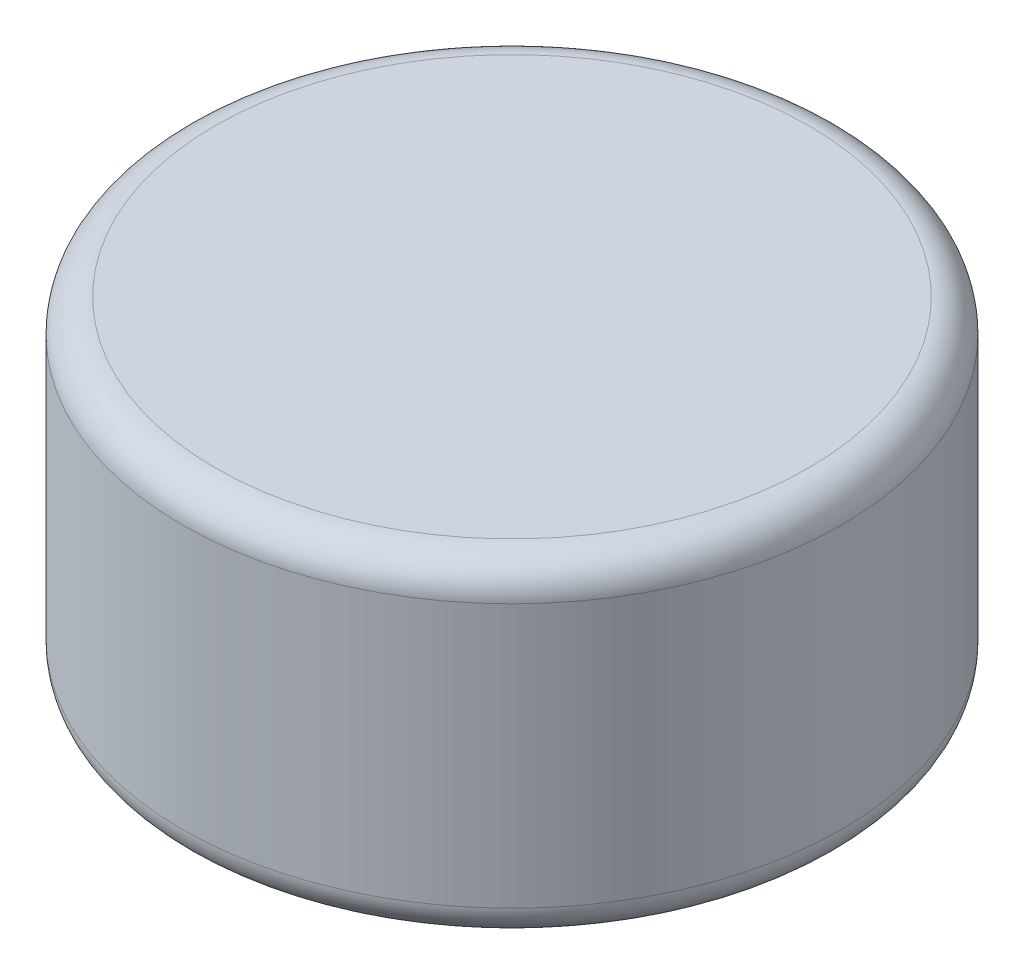
SolidWorks part; units mm, degrees
material "Neodymium Magnet"
ref_plane "Front Plane" through (0, 0, 0) normal (0, 0, 1) x (1, 0, 0)
ref_plane "Top Plane" through (0, 0, 0) normal (0, 1, 0) x (1, 0, 0)
ref_plane "Right Plane" through (0, 0, 0) normal (1, 0, 0) x (0, 0, -1)
sketch "Sketch1" plane through (0, 0, 0) normal (0, 1, 0) x (1, 0, 0)
  circle A0 centre (0, 0) radius 3.175
  dimension "OD" = 6.35
extrude "Boss-Extrude1" add sketch "Sketch1" along normal mid plane 3.175
fillet "Fillet1" radius 0.3175 2 edges at (0, -1.5875, 3.175) (0, 1.5875, 3.175)
equation "\"D1@Fillet1\"=\"Thickness@Boss-Extrude1\"/10"
